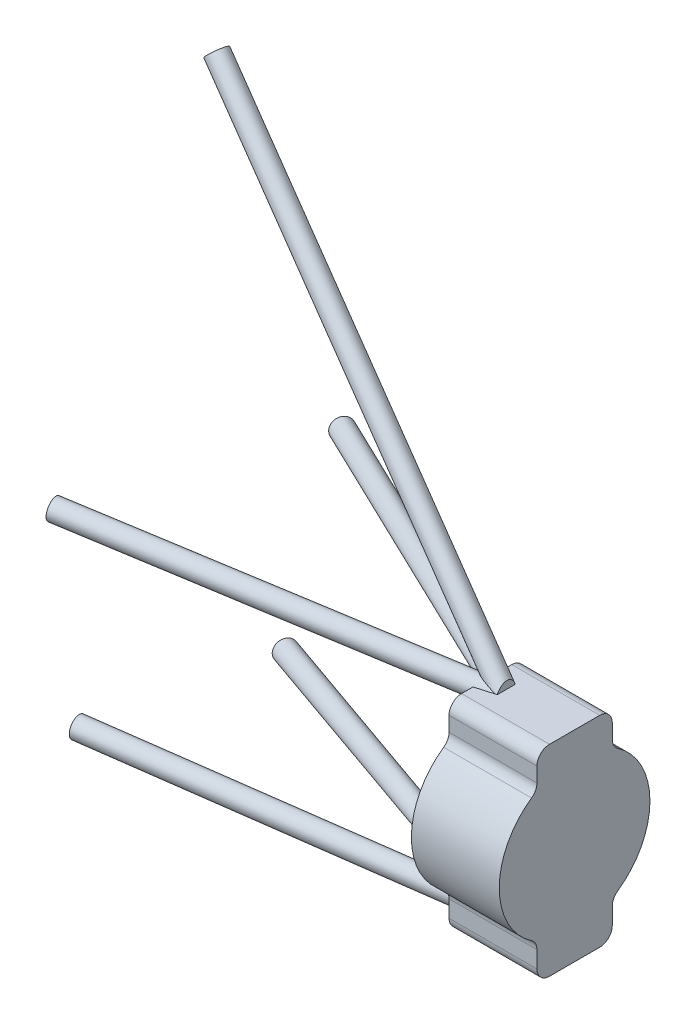
SolidWorks part; units mm, degrees
ref_plane "Front Plane" through (0, 0, 0) normal (0, 0, 1) x (1, 0, 0)
ref_plane "Top Plane" through (0, 0, 0) normal (0, 1, 0) x (1, 0, 0)
ref_plane "Right Plane" through (0, 0, 0) normal (1, 0, 0) x (0, 0, -1)
sketch3d "3DSketch1"
  line L0 (190, 500, -650) -> (480, 230, -590) construction
  line L1 (0, 0, 0) -> (0, 0, -650) construction
  line L2 (0, 0, -650) -> (190, 0, -650) construction
  line L3 (190, 0, -650) -> (190, 500, -650) construction
  line L4 (0, 0, -590) -> (480, 0, -590) construction
  line L5 (480, 0, -590) -> (480, 230, -590) construction
  line L6 (480, 230, -590) -> (190, 190, -750)
  line L7 (480, 230, -590) -> (190, 250, -520)
  line L8 (190, 250, -520) -> (190, 190, -750) construction
  line L9 (0, 0, -520) -> (190, 0, -520) construction
  line L10 (190, 0, -520) -> (190, 250, -520) construction
  line L11 (0, 0, 0) -> (0, 0, -750) construction
  line L12 (0, 0, -750) -> (190, 0, -750) construction
  line L13 (190, 0, -750) -> (190, 190, -750) construction
  dimension "D1" = 190
  dimension "D2" = 650
  dimension "D3" = 500
  dimension "D4" = 590
  dimension "D5" = 480
  dimension "D6" = 230
  dimension "D7" = 250
  dimension "D8" = 520
  dimension "D9" = 750
  dimension "D10" = 190
sketch3d "3DSketch4"
  line L0 (480, 230, -590) -> (190, 500, -650)
sweep "Sweep3" add path "3DSketch1" circular profile diameter 16 parameters "D3"=16
sweep "Sweep4" add path "3DSketch4" circular profile diameter 16 parameters "D3"=16
sketch3d "3DSketch6"
  line L0 (480, 0, -590) -> (480, 80, -590) construction
  line L1 (480, 0, -590) -> (480, 230, -590) construction
  line L2 (480, 80, -590) -> (190, 90, -539.0585)
  line L3 (190, 90, -539.0585) -> (190, 0, -539.0585) construction
  line L4 (190, 0, -539.0585) -> (0, 0, -539.0585) construction
  line L5 (0, 0, 0) -> (0, 0, -650) construction
  line L6 (480, 80, -590) -> (190, 60, -704.5489)
  line L7 (190, 60, -704.5489) -> (190, 0, -704.5489) construction
  line L8 (190, 0, -704.5489) -> (0, 0, -704.5489) construction
  line L9 (0, 0, 0) -> (0, 0, -750) construction
  line L10 (0, 0, -520) -> (190, 0, -520) construction
  line L11 (0, 0, -650) -> (190, 0, -650) construction
  dimension "D1" = 80
  dimension "D2" = 90
  dimension "D3" = 60
sweep "Sweep6" add path "3DSketch6" circular profile diameter 16 parameters "D3"=16
sketch "Sketch80" plane through (0, 0, 0) normal (0, 1, 0) x (1, 0, 0)
  line L1 (480, 619.0948) -> (530, 619.0948)
  line L2 (480, 619.0948) -> (480, 561.2453)
  line L3 (480, 561.2453) -> (530, 561.2453)
  line L4 (530, 619.0948) -> (530, 561.2453)
  dimension "D1" = 480
  dimension "D2" = 50
extrude "Cut-Extrude1" cut sketch "Sketch80" along normal blind 300
ref_plane "Plane2" through (465, 0, 0) normal (1, 0, 0) x (0, 0, -1)
sketch "Sketch81" plane through (465, 0, 0) normal (1, 0, 0) x (0, 0, -1)
  line L0 (590, 0) -> (590, 230) construction
  line L1 (530, 235) -> (650, 235)
  line L2 (530, 235) -> (530, 75)
  line L3 (530, 75) -> (650, 75)
  line L4 (650, 235) -> (650, 75)
  line L5 (560, 207.8363) -> (560, 235)
  line L6 (620, 207.8363) -> (620, 235.6312)
  line L7 (560, 103.9132) -> (560, 75)
  line L8 (620, 103.9132) -> (620, 75)
  circle A0 centre (590, 155.8747) radius 60
  point P4 (590, 235)
  dimension "D4" = 30
  dimension "D1" = 120
  dimension "D2" = 160
  dimension "D3" = 75
  dimension "D5" = 30
  dimension "D6" = 30
  dimension "D7" = 30
extrude "Boss-Extrude1" add sketch "Sketch81" along normal blind 70 contours A0 | A0 L6 L1 L5 | A0 L7 L3 L8
fillet "Fillet1" radius 10 8 edges at (500, 75, -560) (500, 75, -620) (500, 103.9132, -620) (500, 103.9132, -560) (500, 207.8363, -620) (500, 207.8363, -560) (500, 235, -620) (500, 235, -560)
combine bodies "Combine1" operation type add bodies to combine 109 108
move or copy body "Body-Move/Copy1" bodies to move or copy 110 copy no translate (0, 46, 0)
